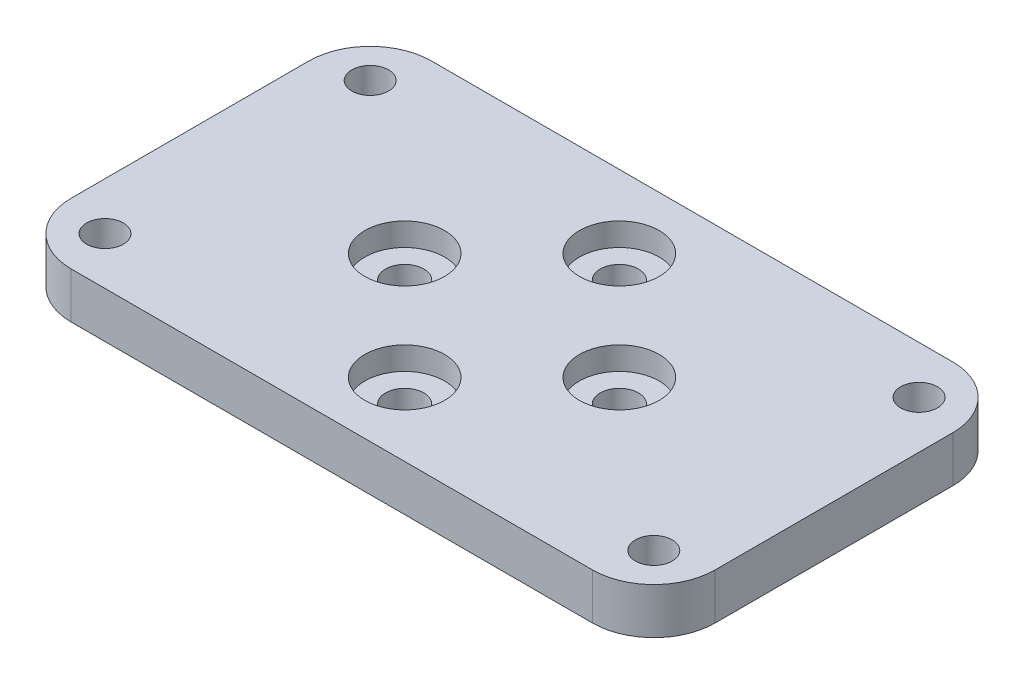
SolidWorks part; units mm, degrees
ref_plane "前视基准面" through (0, 0, 0) normal (0, 0, 1) x (1, 0, 0)
ref_plane "上视基准面" through (0, 0, 0) normal (0, 1, 0) x (1, 0, 0)
ref_plane "右视基准面" through (0, 0, 0) normal (1, 0, 0) x (0, 0, -1)
other "Configuration Table"
sketch "草图1" plane through (0, 0, 0) normal (0, 1, 0) x (1, 0, 0)
  line L0 (-13.2993, 0) -> (13.5934, 0) construction
  line L1 (0, 16.6571) -> (0, -12.7411) construction
  line L3 (21, -11.75) -> (-21, -11.75)
  line L4 (21, -11.75) -> (21, 11.75)
  line L5 (21, 11.75) -> (-21, 11.75)
  line L6 (-21, -11.75) -> (-21, 11.75)
  line L7 (21, -11.75) -> (-21, 11.75) construction
  line L8 (21, 11.75) -> (-21, -11.75) construction
  circle A0 centre (0, 0) radius 7 construction
  circle A1 centre (7, 0) radius 1.25
  circle A2 centre (0, -7) radius 1.25
  circle A3 centre (-7, 0) radius 1.25
  circle A4 centre (0, 7) radius 1.25
  circle A5 centre (-17.9, 8.65) radius 1.2
  circle A6 centre (17.9, 8.65) radius 1.2
  circle A7 centre (-17.9, -8.65) radius 1.2
  circle A8 centre (17.9, -8.65) radius 1.2
  point P18 (0, 0)
  dimension "D1" = 14
  dimension "D2" = 2.5
  dimension "D4" = 35.8
  dimension "D5" = 17.3
  dimension "D6" = 2.4
  dimension "D7" = 42
  dimension "D8" = 23.5
  dimension "D3" = 4
extrude "凸台-拉伸1" add sketch "草图1" along normal blind 3
fillet "圆角1" radius 4 4 edges at (-21, 1.5, -11.75) (-21, 1.5, 11.75) (21, 1.5, 11.75) (21, 1.5, -11.75)
sketch "草图2" plane through (0, 3, 0) normal (0, 1, 0) x (1, 0, 0)
  circle A0 centre (7, 0) radius 2.6
  circle A1 centre (0, -7) radius 2.6
  circle A2 centre (-7, 0) radius 2.6
  circle A3 centre (0, 7) radius 2.6
  point P12 (0, 0)
  dimension "D1" = 5.2
  dimension "D2" = 4
extrude "切除-拉伸1" cut sketch "草图2" against normal blind 1.5
